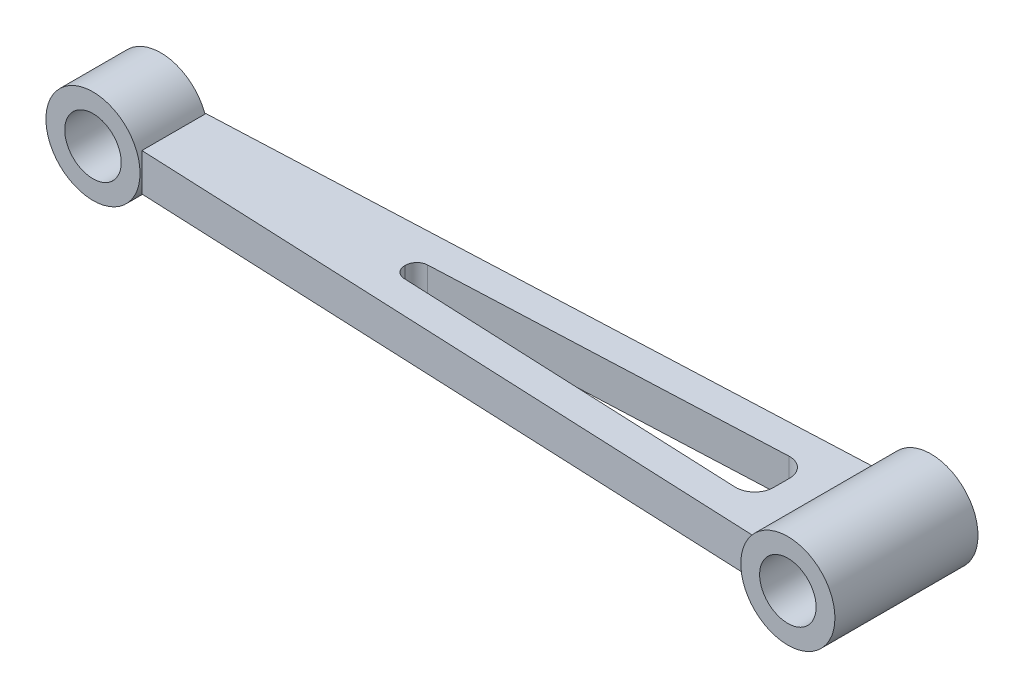
SolidWorks part; units mm, degrees
ref_plane "Front Plane" through (0, 0, 0) normal (0, 0, 1) x (1, 0, 0)
ref_plane "Top Plane" through (0, 0, 0) normal (0, 1, 0) x (1, 0, 0)
ref_plane "Right Plane" through (0, 0, 0) normal (1, 0, 0) x (0, 0, -1)
sketch "Sketch2" plane through (0, 0, 0) normal (0, 1, 0) x (1, 0, 0)
  line L1 (0, 8.5) -> (169.56, 15.9031)
  line L2 (169.56, 15.9031) -> (169.56, -15.9031)
  line L3 (169.56, -15.9031) -> (0, -8.5)
  line L5 (0, 0) -> (339.12, 0) construction
  line L6 (0, 0) -> (-12.5, 0) construction
  line L7 (-12.5, 16.4267) -> (-12.5, 0) construction
  line L8 (-30.0566, 7.1877) -> (-30.0566, -7.1877) construction
  line L9 (0, 8.5) -> (0, -8.5)
  line L10 (17.8649, 9.28) -> (17.8649, -9.28) construction
  line L11 (61.39, 0) -> (61.39, 0.1281)
  line L12 (64.2591, 3.1253) -> (156.1719, 7.1383)
  line L13 (161.39, 2.143) -> (161.39, -2.143)
  line L14 (156.1719, -7.1383) -> (64.2591, -3.1253)
  line L15 (61.39, -0.1281) -> (61.39, 0)
  line L16 (182.06, 22.7702) -> (182.06, -23.121) construction
  line L17 (61.39, 0) -> (64.39, 0)
  arc A0 (161.39, -2.143) -> (156.1719, -7.1383) centre (156.39, -2.143) cw
  arc A1 (161.39, 2.143) -> (156.1719, 7.1383) centre (156.39, 2.143) ccw
  arc A2 (64.2591, -3.1253) -> (61.39, -0.1281) centre (64.39, -0.1281) cw
  arc A3 (61.39, 0.1281) -> (64.2591, 3.1253) centre (64.39, 0.1281) cw
  point P6 (169.56, 0)
  point P28 (61.39, -3)
  point P31 (61.39, 3)
  dimension "D9" = 5
  dimension "D12" = 3
  dimension "D1" = 17
  dimension "D2" = 169.56
  dimension "D3" = 5
  dimension "D4" = 12.5
  dimension "D5" = 18.56
  dimension "D6" = 100
  dimension "D7" = 12.5
  dimension "D8" = 20.67
  dimension "D10" = 6
  dimension "D11" = 3
extrude "Boss-Extrude1" add sketch "Sketch2" against normal blind 10 contours L1 L9 L3 L2 L11 A3 L12 A1 L13 A0 L14 A2 L15
sketch "Sketch3" plane through (0, 0, 0) normal (0, 0, 1) x (1, 0, 0)
  line L0 (0, -5) -> (-12.5, -5) construction
  line L1 (0, -10) -> (0, 0) construction
  line L2 (-12.5, 7.8325) -> (-12.5, -5) construction
  circle A0 centre (-12.5, -5) radius 12.5
  circle A1 centre (-12.5, -5) radius 7.5
  dimension "D2" = 15
  dimension "D1" = 12.5
extrude "Boss-Extrude2" add sketch "Sketch3" along normal mid plane 18 separate body
sketch "Sketch4" plane through (0, 0, 0) normal (0, 0, 1) x (1, 0, 0)
  line L0 (169.56, -5) -> (214.7859, -5) construction
  line L1 (169.56, -10) -> (169.56, 0) construction
  circle A0 centre (182.06, -5) radius 12.5
  circle A1 centre (182.06, -5) radius 7.5
  dimension "D2" = 25
  dimension "D3" = 15
  dimension "D1" = 12.5
extrude "Boss-Extrude3" add sketch "Sketch4" along normal mid plane 38 separate body
